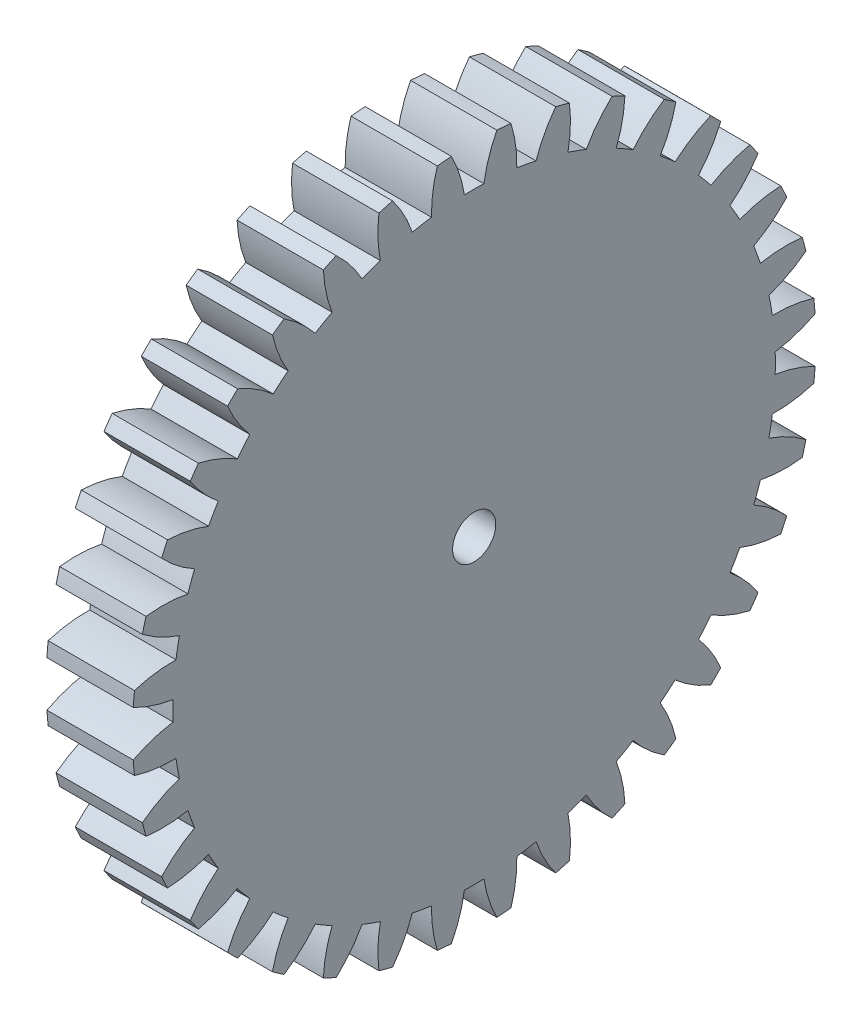
SolidWorks part; units mm, degrees
ref_plane "Plane1" through (0, 0, 0) normal (0, 0, 1) x (1, 0, 0)
ref_plane "Plane2" through (0, 0, 0) normal (0, 1, 0) x (1, 0, 0)
ref_plane "Plane3" through (0, 0, 0) normal (1, 0, 0) x (0, 0, -1)
sketch "HoldingSke" plane through (0, 0, 0) normal (0, 1, 0) x (1, 0, 0)
  line L0 (0, 0) -> (0.3236, -0.2351)
  line L1 (-15, 0) -> (100, 0) construction
  line L2 (0, 0) -> (-2.1039, 2.3779)
  line L3 (0, 0) -> (-11.863, 4.5341)
  line L4 (0, 0) -> (6.9867, 5.0761)
  line L5 (0, 0) -> (-46.8476, -17.4728)
  line L6 (0, 0) -> (-9.9476, -6.7116)
  line L7 (-2.1039, 2.3779) -> (8.6586, 51.2059)
  line L8 (-76.2, 54.61) -> (-74.8, 54.61)
  line L9 (-67.7845, 28.3722) -> (-49.3413, 33.142)
  line L10 (-76.2, 71.12) -> (104.1128, 71.12)
  line L11 (0, 0) -> (-12, 0)
  line L12 (-76.2, 101.6) -> (-76.113, 101.6)
  line L13 (24.9733, 27.94) -> (52.9518, 28.4284)
  line L14 (24.9733, 27.94) -> (24.9743, 27.94)
  line L15 (24.9733, 27.94) -> (100.4006, 29.5858)
  line L16 (-63.627, -2.5) -> (-12.827, -2.5)
  circle A0 centre (0, 0) radius 4
  circle A1 centre (0, 0) radius 37.5
  circle A2 centre (0, 0) radius 37.5
  circle A3 centre (0, 0) radius 4
  dimension "MHD" = 75
  dimension "Hub_dia" = 75
  dimension "Bore" = 8
  dimension "MBD" = 8
  dimension "Num_teeth" = 36
  dimension "Pitch" = 0.4
  dimension "Overall_len" = 50
  dimension "Show_teeth" = 36
  dimension "Thickness" = 12
  dimension "OAL" = 50.0001
  dimension "T_dim" = 1.4
  dimension "Ap" = 14.5
  dimension "H" = 19.05
  dimension "Pitch_radius" = 180.3128
  dimension "Width" = 12
  dimension "Backlash" = 0.087
  dimension "Addendum_fac" = 1
  dimension "Dedendum_fac" = 1.25
  dimension "Clearance_fac" = 0.25
  dimension "Dedendum_add" = 0.001
  dimension "Module" = 2.5
sketch "BasProSke" plane through (0, 0, 0) normal (0, 1, 0) x (1, 0, 0)
  line L0 (-10, 0) -> (60, 0) construction
  line L1 (0, 0) -> (0, 47.5)
  line L2 (0, 0) -> (12, 0)
  line L3 (12, 0) -> (12, 47.5)
  line L4 (12, 47.5) -> (0, 47.5)
  dimension "Thickness" = 12
  dimension "Diameter" = 95
revolve "Base-Revolve" add sketch "BasProSke" angle 360 about L0
sketch "TooCutSke" plane through (0, 0, 0) normal (1, 0, 0) x (0, 0, -1)
  line L1 (0, 0) -> (0, 107) construction
  line L2 (0, 0) -> (-2.1151, 44.9503) construction
  line L3 (0, 0) -> (-7.8377, 89.5849) construction
  line L4 (-2.1151, 44.9503) -> (-3.9188, 44.7925) construction
  arc A0 (1.3557, 41.852) -> (-1.3557, 41.852) centre (0, 0) ccw
  arc A1 (3.1701, 47.4196) -> (-3.1701, 47.4196) centre (0, 0) ccw
  circle A2 centre (0, 0) radius 45 construction
  circle A3 centre (0, 0) radius 43.5666 construction
  arc A4 (-1.3557, 41.852) -> (-3.1701, 47.4196) centre (-19.1491, 39.1327) ccw
  arc A5 (3.1701, 47.4196) -> (1.3557, 41.852) centre (19.1491, 39.1327) ccw
  dimension "Root_dia" = 83.748
  dimension "Overcut_dia" = 95.0508
  dimension "Pitch_dia" = 90
  dimension "Base_dia" = 87.1333
  dimension "Flank_rad" = 18
  dimension "Half_ang" = 5
  dimension "Half_CT" = 1.8106
extrude "ToothCut" cut sketch "TooCutSke" along normal through all
fillet "Breaks" [suppressed] radius 0.05
fillet "RootFillets" [suppressed] radius 0.626
pattern_circular "TeethCuts" count 36 every 10 about axis through (-10, 0, 0) along (1, 0, 0) of "ToothCut", "RootFillets", "Breaks"
sketch "HubNeaOneSke" plane through (0, 0, 0) normal (-1, 0, 0) x (0, 0, 1)
  circle A0 centre (0, 0) radius 37.5
  dimension "Diameter" = 75
extrude "HubNearOne" [suppressed] add sketch "HubNeaOneSke" along normal blind 38.0001
sketch "HubNeaBotSke" plane through (0, 0, 0) normal (-1, 0, 0) x (0, 0, 1)
  circle A0 centre (0, 0) radius 37.5
  dimension "Diameter" = 75
extrude "HubNearBoth" [suppressed] add sketch "HubNeaBotSke" along normal blind 19
ref_plane "FarPln" through (12, 0, 0) normal (1, 0, 0) x (0, 0, -1)
sketch "HubFarSke" plane through (12, 0, 0) normal (1, 0, 0) x (0, 0, -1)
  circle A0 centre (0, 0) radius 37.5
  dimension "Diameter" = 75
extrude "HubFar" [suppressed] add sketch "HubFarSke" along normal blind 19
sketch "BorSke" plane through (0, 0, 0) normal (1, 0, 0) x (0, 0, -1)
  circle A0 centre (0, 0) radius 4
  dimension "Diameter" = 8
extrude "Bore" cut sketch "BorSke" along normal mid plane 100.0001
sketch "KeySke" plane through (0, 0, 0) normal (1, 0, 0) x (0, 0, -1)
  line L0 (-1.5, 0) -> (-1.5, 5.4)
  line L1 (-1.5, 5.4) -> (1.5, 5.4)
  line L2 (1.5, 5.4) -> (1.5, 0)
  line L3 (0, 0) -> (0, 34) construction
  line L4 (-1.5, 0) -> (1.5, 0)
  dimension "Offset" = 5.4
  dimension "Width" = 3
extrude "Keyway" cut sketch "KeySke" along normal mid plane 100.0001
pattern_circular "Keyway2" count 2 every 90 about axis through (0, 0, 0) along (1, 0, 0) of "Keyway"
sketch "Sketch1" plane through (12, 0, 0) normal (1, 0, 0) x (0, 0, -1)
  circle A0 centre (0, 0) radius 6
  circle A2 centre (0, 0) radius 3
  point P3 (0, 0)
extrude "Boss-Extrude1" add sketch "Sketch1" against normal blind 20
sketch "Sketch2" plane through (0, 0, 0) normal (0, 1, 0) x (1, 0, 0)
  circle A0 centre (-5, 0) radius 1.5
  point P2 (0, 0)
  point P3 (0, 0)
extrude "Cut-Extrude1" cut sketch "Sketch2" against normal blind 15 and the other way blind 10
equation "' \"Module@HoldingSke\" = 6.35"
equation "' \"Num_teeth@HoldingSke\" = 12"
equation "' \"Ap@HoldingSke\" =  20"
equation "' \"Ap@HoldingSke\" = 20"
equation "' \"Width@HoldingSke\" = 0.5 * 25.4"
equation "' \"Hub_dia@HoldingSke\"= 1 * 25.4"
equation "' \"Hub_dia@HoldingSke\" = 1 * 25.4"
equation "' \"Overall_len@HoldingSke\" = 1.0 * 25.4"
equation "' \"Bore@HoldingSke\" = 0.75 * 25.4"
equation "' \"T_dim@HoldingSke\" = 0.1 * 25.4"
equation "' \"Width@KeySke\" = 0.25 * 25.4"
equation "' \"Show_teeth@HoldingSke\" = 13"
equation "' \"Backlash@HoldingSke\" = 0.009 * 25.4"
equation "' \"Addendum_fac@HoldingSke\" = 1.0"
equation "' \"Dedendum_fac@HoldingSke\" = 1.25"
equation "' \"Dedendum_add@HoldingSke\" = 0.00005 * 25.4"
equation "' \"Clearance_fac@HoldingSke\" = 0.25"
equation "\"Pitch@HoldingSke\" = 1 / \"Module@HoldingSke\""
equation "\"Overcut_dia@TooCutSke\" = (\"Num_teeth@HoldingSke\" + 2 * \"Addendum_fac@HoldingSke\") / \"Pitch@HoldingSke\" + 0.002 * 25.4"
equation "\"Pitch_dia@TooCutSke\" = \"Num_teeth@HoldingSke\" / \"Pitch@HoldingSke\""
equation "\"Base_dia@TooCutSke\" = \"Num_teeth@HoldingSke\" / \"Pitch@HoldingSke\" * cos((\"Ap@HoldingSke\"  * 3.14159265 / 180))"
equation "\"Root_dia@TooCutSke\" = (\"Num_teeth@HoldingSke\" + 2) / \"Pitch@HoldingSke\" - 2 * (\"Addendum_fac@HoldingSke\" + \"Dedendum_fac@HoldingSke\") / \"Pitch@HoldingSke\" - \"Dedendum_add@HoldingSke\" * 2"
equation "\"Half_ang@TooCutSke\" = 180 / \"Num_teeth@HoldingSke\""
equation "\"Half_CT@TooCutSke\" = \"Num_teeth@HoldingSke\" / \"Pitch@HoldingSke\" * sin((3.14159265 / 2 / \"Num_teeth@HoldingSke\")) / 2 - 7 * \"Backlash@HoldingSke\" / 4"
equation "\"Flank_rad@TooCutSke\" = \"Num_teeth@HoldingSke\" / \"Pitch@HoldingSke\" / 5"
equation "\"Radius@RootFillets\" = \"Clearance_fac@HoldingSke\" / \"Pitch@HoldingSke\" + \"Dedendum_add@HoldingSke\""
equation "\"Break_rad@Breaks\" = 0.02 / \"Pitch@HoldingSke\""
equation "\"Thickness@HoldingSke\" = \"Width@HoldingSke\""
equation "\"OAL@HoldingSke\" = \"Thickness@HoldingSke\""
equation "\"MHD@HoldingSke\" = (\"Num_teeth@HoldingSke\" + 2) / \"Pitch@HoldingSke\" - 2 * (\"Addendum_fac@HoldingSke\" + \"Dedendum_fac@HoldingSke\")  / \"Pitch@HoldingSke\" - \"Dedendum_add@HoldingSke\" * 2"
equation "\"MBD@HoldingSke\" = (\"Num_teeth@HoldingSke\" + 2) / \"Pitch@HoldingSke\" - 2 * (\"Addendum_fac@HoldingSke\" + \"Dedendum_fac@HoldingSke\")  / \"Pitch@HoldingSke\" - \"Dedendum_add@HoldingSke\" * 2 - 0.002 * 25.4"
equation "\"MHD@HoldingSke\" = ((sgn( \"MHD@HoldingSke\" - \"Hub_dia@HoldingSke\" )-1)*( \"MHD@HoldingSke\" - \"Hub_dia@HoldingSke\" ))/-2+ \"Hub_dia@HoldingSke\""
equation "\"MBD@HoldingSke\" = ((sgn( \"MBD@HoldingSke\" - \"Bore@HoldingSke\" )-1)*( \"MBD@HoldingSke\" - \"Bore@HoldingSke\" ))/-2+ \"Bore@HoldingSke\""
equation "\"OAL@HoldingSke\" = ((sgn( \"OAL@HoldingSke\" - \"Overall_len@HoldingSke\" )+1)*( \"OAL@HoldingSke\" - \"Overall_len@HoldingSke\" ))/2 + \"Overall_len@HoldingSke\" + 0.000002 * 25.4"
equation "\"Num_teeth@TeethCuts\" = int( \"Show_teeth@HoldingSke\" ) + 1"
equation "\"Num_teeth@TeethCuts\" = ((sgn( \"Num_teeth@TeethCuts\" - \"Num_teeth@HoldingSke\" )-1)*( \"Num_teeth@TeethCuts\" - \"Num_teeth@HoldingSke\" ))/-2+ \"Num_teeth@HoldingSke\""
equation "\"Num_teeth@TeethCuts\" = ((sgn( \"Num_teeth@TeethCuts\" - 2.0)+1)*( \"Num_teeth@TeethCuts\" - 2.0))/2 +2.0"
equation "\"Angle@TeethCuts\" = 360.0 / \"Num_teeth@HoldingSke\""
equation "\"Diameter@BasProSke\" = (\"Num_teeth@HoldingSke\" + 2 * \"Addendum_fac@HoldingSke\") / \"Pitch@HoldingSke\""
equation "\"Thickness@BasProSke\"  = \"Thickness@HoldingSke\""
equation "' \"Fillet_rad@BasProSke\" =  \"Thickness@HoldingSke\" * 0.05"
equation "' \"Fillet_rad@BasProSke\" = \"Thickness@HoldingSke\" * 0.05"
equation "\"MHD@HoldingSke\" = ((sgn( \"MHD@HoldingSke\" - \"Root_dia@TooCutSke\" )-1)*( \"MHD@HoldingSke\" - \"Root_dia@TooCutSke\" ))/-2+ \"Root_dia@TooCutSke\""
equation "\"Diameter@HubNeaOneSke\" = \"MHD@HoldingSke\""
equation "\"Length@HubNearOne\" = \"OAL@HoldingSke\" - \"Thickness@BasProSke\""
equation "\"Diameter@HubNeaBotSke\" = \"MHD@HoldingSke\""
equation "\"Length@HubNearBoth\" = ( \"OAL@HoldingSke\" - \"Thickness@BasProSke\" ) / 2.0"
equation "\"Thickness@FarPln\" = \"Thickness@BasProSke\""
equation "\"Diameter@HubFarSke\" = \"MHD@HoldingSke\""
equation "\"Length@HubFar\" = ( \"OAL@HoldingSke\" - \"Thickness@BasProSke\" ) / 2.0"
equation "\"Diameter@BorSke\" = \"MBD@HoldingSke\""
equation "\"D1@Bore\" = \"OAL@HoldingSke\" * 2.0"
equation "\"D1@Keyway\" = \"OAL@HoldingSke\" * 2.0"
equation "\"Offset@KeySke\" = \"T_dim@HoldingSke\" + \"MBD@HoldingSke\" / 2.0"
